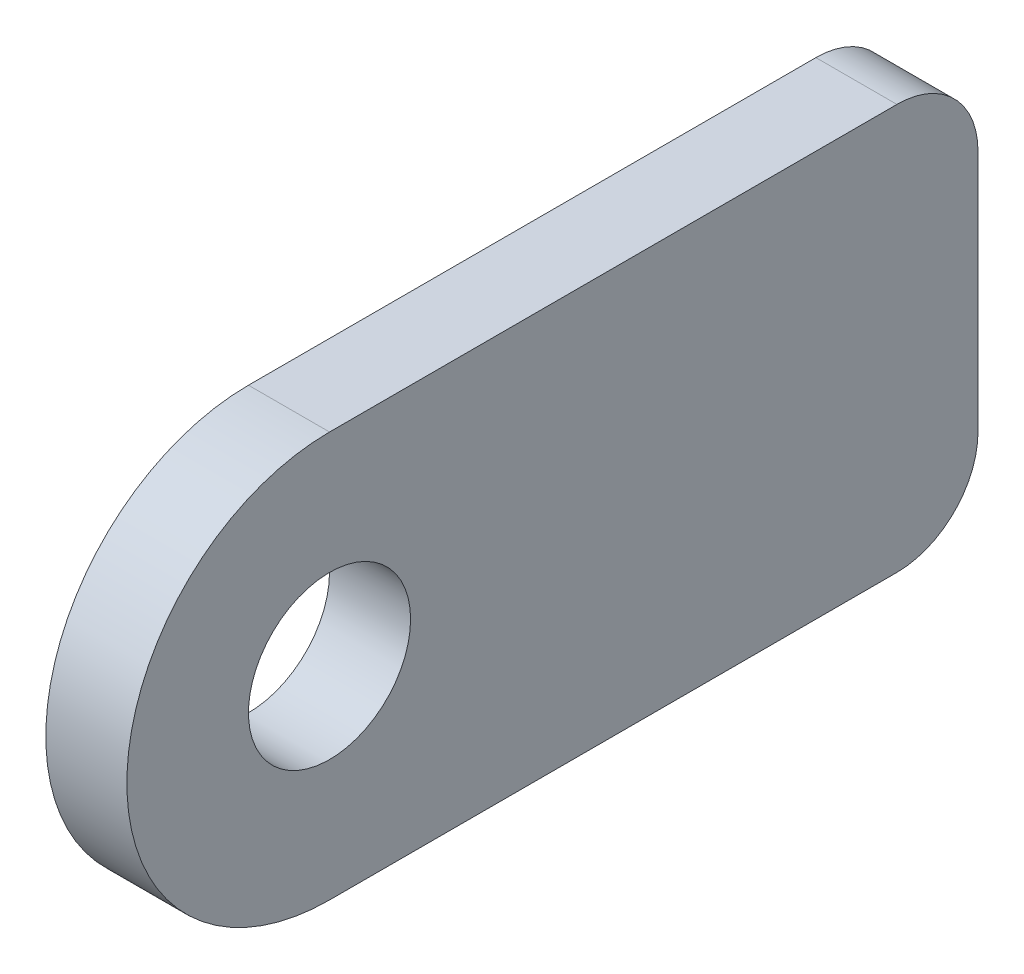
SolidWorks part; units mm, degrees
ref_plane "Front Plane" through (0, 0, 0) normal (0, 0, 1) x (1, 0, 0)
ref_plane "Top Plane" through (0, 0, 0) normal (0, 1, 0) x (1, 0, 0)
ref_plane "Right Plane" through (0, 0, 0) normal (1, 0, 0) x (0, 0, -1)
sketch "Sketch1" plane through (0, 0, 0) normal (1, 0, 0) x (0, 0, -1)
  line L0 (10, -25) -> (-5, -25) construction
  line L1 (20, 0) -> (100, 0)
  line L3 (20, -50) -> (100, -50)
  line L4 (100, 0) -> (100, -50)
  circle A0 centre (20, -25) radius 10
  arc A1 (20, 0) -> (20, -50) centre (20, -25) ccw
  dimension "D3" = 15
  dimension "D1" = 25
  dimension "D2" = 50
  dimension "D4" = 25
extrude "Boss-Extrude1" add sketch "Sketch1" along normal blind 10
fillet "Fillet1" radius 10 2 edges at (5, 0, -100) (5, -50, -100)
